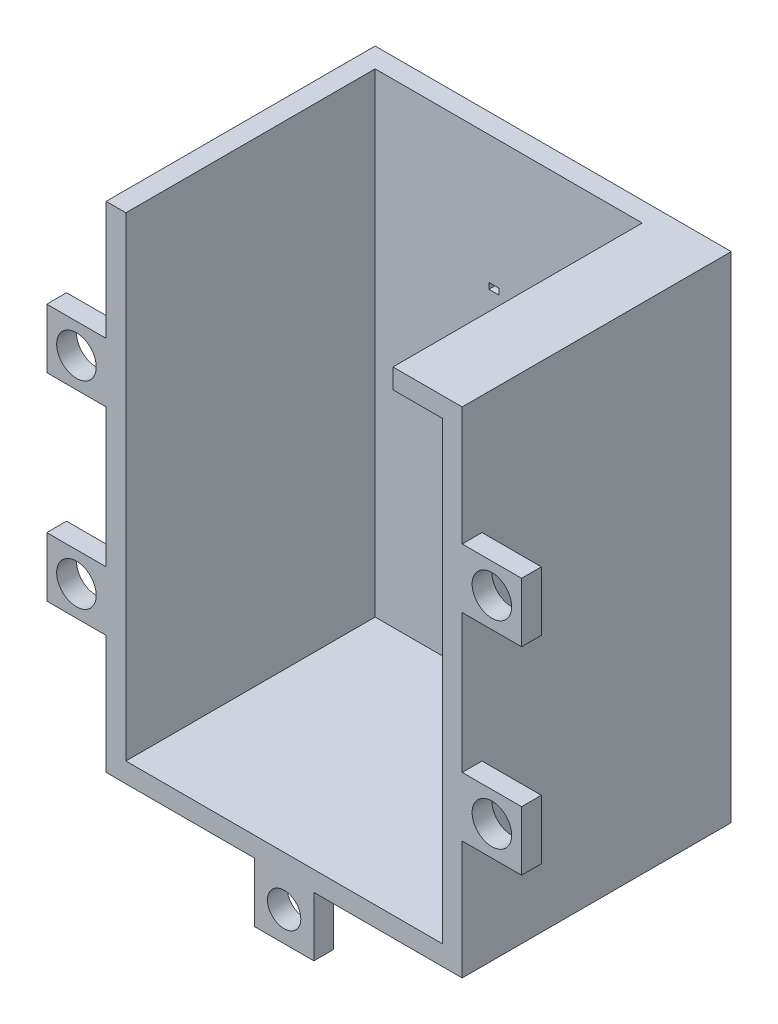
SolidWorks part; units mm, degrees
ref_plane "Front Plane" through (0, 0, 0) normal (0, 0, 1) x (1, 0, 0)
ref_plane "Top Plane" through (0, 0, 0) normal (0, 1, 0) x (1, 0, 0)
ref_plane "Right Plane" through (0, 0, 0) normal (1, 0, 0) x (0, 0, -1)
sketch "Sketch1" plane through (0, 0, 0) normal (0, 0, 1) x (1, 0, 0)
  line L0 (0, 0) -> (0, 50)
  line L1 (0, 50) -> (36, 50)
  line L2 (36, 50) -> (36, 0)
  line L3 (36, 0) -> (0, 0)
  dimension "D1" = 50
  dimension "D2" = 36
extrude "Boss-Extrude1" add sketch "Sketch1" against normal blind 27.2
sketch "Sketch2" plane through (0, 0, 0) normal (0, 0, 1) x (1, 0, 0)
  line L0 (18, 50) -> (18, 0) construction
  line L1 (36, 50) -> (0, 50) construction
  line L2 (0, 0) -> (36, 0) construction
  circle A0 centre (18, 33) radius 3
  dimension "D1" = 6
  dimension "D2" = 17
extrude "Cut-Extrude1" cut sketch "Sketch2" against normal up to next
sketch "Sketch8" plane through (0, 0, 0) normal (0, 0, 1) x (1, 0, 0)
  line L0 (2, 48) -> (34, 48)
  line L1 (34, 48) -> (34, 2)
  line L2 (34, 2) -> (2, 2)
  line L3 (2, 2) -> (2, 48)
  line L4 (36, 50) -> (0, 50) construction
  line L5 (0, 50) -> (0, 0) construction
  dimension "D1" = 32
  dimension "D2" = 46
  dimension "D3" = 2
  dimension "D4" = 2
extrude "Cut-Extrude2" cut sketch "Sketch8" against normal blind 25.2
sketch "Sketch9" plane through (0, 0, -27.2) normal (0, 0, -1) x (-1, 0, 0)
  circle A0 centre (-18, 33) radius 5.25 construction
  dimension "D1" = 10.5
sketch "Sketch10" plane through (0, 0, -27.2) normal (0, 0, -1) x (-1, 0, 0)
  circle A0 centre (-18, 20.75) radius 7 construction
  dimension "D1" = 14
  dimension "D2" = 12.25
sketch "Sketch11" plane through (0, 0, -27.2) normal (0, 0, -1) x (-1, 0, 0)
  line L0 (-13, 13.55) -> (-23, 13.55) construction
  line L1 (-23, 13.55) -> (-23, 22.75) construction
  line L2 (-23, 22.75) -> (-13, 22.75) construction
  line L3 (-13, 22.75) -> (-13, 13.55) construction
  dimension "D1" = 7.2
  dimension "D2" = 2
  dimension "D3" = 5
  dimension "D4" = 5
sketch "Sketch12" plane through (0, 0, -27.2) normal (0, 0, -1) x (-1, 0, 0)
  line L0 (-13.5, 13.55) -> (-13.5, 12.95)
  line L1 (-13, 13.55) -> (-23, 13.55) construction
  line L2 (-13.5, 12.95) -> (-14.5, 12.95)
  line L3 (-14.5, 12.95) -> (-14.5, 13.55)
  line L4 (-14.5, 13.55) -> (-13.5, 13.55)
  line L5 (-17.5, 13.55) -> (-18.5, 13.55)
  line L6 (-18.5, 13.55) -> (-18.5, 12.95)
  line L7 (-18.5, 12.95) -> (-17.5, 12.95)
  line L8 (-17.5, 12.95) -> (-17.5, 13.55)
  line L9 (-21.5, 13.55) -> (-21.5, 12.95)
  line L10 (-21.5, 12.95) -> (-22.5, 12.95)
  line L11 (-22.5, 12.95) -> (-22.5, 13.55)
  line L12 (-22.5, 13.55) -> (-21.5, 13.55)
  line L13 (-12.6, 22.75) -> (-12.6, 23.95)
  line L14 (-12.6, 23.95) -> (-13.4, 23.95)
  line L15 (-13.4, 23.95) -> (-13.4, 22.75)
  line L16 (-13, 22.75) -> (-13, 13.55) construction
  line L17 (-13.4, 22.75) -> (-12.6, 22.75)
  line L18 (-23.4, 22.75) -> (-22.6, 22.75)
  line L19 (-22.6, 22.75) -> (-22.6, 23.95)
  line L20 (-22.6, 23.95) -> (-23.4, 23.95)
  line L21 (-23.4, 23.95) -> (-23.4, 22.75)
  line L22 (-23, 13.55) -> (-23, 22.75) construction
  line L23 (-23, 22.75) -> (-13, 22.75) construction
  dimension "D1" = 1
  dimension "D2" = 0.6
  dimension "D3" = 0.5
  dimension "D4" = 1
  dimension "D5" = 0.6
  dimension "D6" = 4.5
  dimension "D7" = 1
  dimension "D8" = 0.6
  dimension "D9" = 0.5
  dimension "D10" = 1.2
  dimension "D11" = 0.8
  dimension "D12" = 0.8
  dimension "D13" = 1.2
  dimension "D14" = 0.4
  dimension "D15" = 0.4
extrude "Cut-Extrude3" cut sketch "Sketch12" against normal blind 25.2
sketch "Sketch14" plane through (0, 0, 0) normal (0, -1, 0) x (1, 0, 0)
  line L0 (2, 0) -> (2, -25.2)
  line L1 (0, 0) -> (36, 0) construction
  line L2 (2, -25.2) -> (34, -25.2)
  line L3 (34, -25.2) -> (34, 0)
  line L4 (34, 0) -> (2, 0)
  line L5 (0, -27.2) -> (0, 0) construction
  line L6 (0, -27.2) -> (36, -27.2) construction
  line L7 (36, -27.2) -> (36, 0) construction
  dimension "D1" = 2
  dimension "D2" = 2
  dimension "D3" = 2
extrude "Cut-Extrude4" cut sketch "Sketch14" against normal blind 25.2
sketch "Sketch16" plane through (0, 0, 0) normal (0, -1, 0) x (-1, 0, 0)
  line L1 (-34, 25.2) -> (-29, 25.2)
  line L2 (-34, 25.2) -> (-34, 0)
  line L3 (-34, 0) -> (-29, 0)
  line L4 (-29, 25.2) -> (-29, 0)
  dimension "D1" = 5
extrude "Boss-Extrude2" add sketch "Sketch16" against normal blind 2
sketch "Sketch17" plane through (0, 0, 0) normal (0, 0, 1) x (1, 0, 0)
  line L0 (36, 38) -> (42, 38)
  line L1 (36, 0) -> (36, 50) construction
  line L2 (42, 38) -> (42, 32)
  line L3 (42, 32) -> (36, 32)
  line L4 (36, 32) -> (36, 38)
  point P4 (42, 35)
  dimension "D1" = 6
  dimension "D2" = 6
  dimension "D3" = 15
extrude "Boss-Extrude3" add sketch "Sketch17" against normal blind 2 separate body
sketch "Sketch18" plane through (0, 0, 0) normal (0, 0, 1) x (1, 0, 0)
  line L0 (42, 35) -> (36, 35) construction
  line L1 (42, 32) -> (42, 38) construction
  line L2 (36, 38) -> (36, 32) construction
  circle A0 centre (39, 35) radius 2
  dimension "D1" = 4
extrude "Cut-Extrude5" cut sketch "Sketch18" against normal blind 2
ref_plane "Plane4" through (0, 25, 0) normal (0, -1, 0) x (-1, 0, 0)
mirror "Mirror1" about plane through (0, 25, 0) normal (0, -1, 0) of bodies 108
ref_plane "Plane5" through (18, 0, 0) normal (-1, 0, 0) x (0, 0, 1)
mirror "Mirror2" about plane through (18, 0, 0) normal (-1, 0, 0) of bodies 108 109
sketch "Sketch20" plane through (0, 0, 0) normal (0, 0, 1) x (1, 0, 0)
  line L0 (21, 50) -> (21, 56)
  line L1 (36, 50) -> (0, 50) construction
  line L2 (21, 56) -> (15, 56)
  line L3 (15, 56) -> (15, 50)
  line L4 (15, 50) -> (21, 50)
  dimension "D1" = 6
  dimension "D2" = 6
  dimension "D3" = 15
extrude "Boss-Extrude4" add sketch "Sketch20" against normal blind 2
sketch "Sketch21" plane through (0, 0, 0) normal (0, 0, 1) x (1, 0, 0)
  line L0 (21, 50) -> (21, 56) construction
  line L2 (21, 56) -> (15, 56) construction
  circle A0 centre (18, 53) radius 1.6844
  dimension "D1" = 3
  dimension "D2" = 3
extrude "Cut-Extrude6" cut sketch "Sketch21" against normal up to next (2 mm away)
ref_plane "Plane7" through (0, 0, 0) normal (0, -1, 0) x (-1, 0, 0)
combine bodies "Combine1" operation type add bodies to combine 113 109 108 110 111
mirror "Mirror6" about plane through (0, 0, 0) normal (0, -1, 0) of bodies 123
delete or keep bodies "Body-Delete/Keep 3" type delete bodies bodies 123
